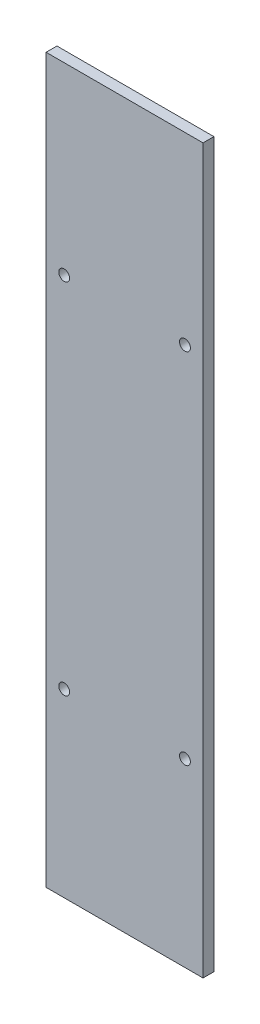
SolidWorks part; units mm, degrees
ref_plane "正面" through (0, 0, 0) normal (0, 0, 1) x (1, 0, 0)
ref_plane "平面" through (0, 0, 0) normal (0, 1, 0) x (1, 0, 0)
ref_plane "右側面" through (0, 0, 0) normal (1, 0, 0) x (0, 0, -1)
sketch "ｽｹｯﾁ1" plane through (0, 0, 0) normal (0, 0, 1) x (1, 0, 0)
  line L0 (0, 0) -> (0, 49.5573) construction
  line L1 (16.7, -49.5573) -> (-16.7, -49.5573) construction
  line L2 (16.7, -49.5573) -> (16.7, 49.5573) construction
  line L3 (16.7, 49.5573) -> (-16.7, 49.5573) construction
  line L4 (-16.7, -49.5573) -> (-16.7, 49.5573) construction
  line L5 (16.7, -49.5573) -> (-16.7, 49.5573) construction
  line L6 (16.7, 49.5573) -> (-16.7, -49.5573) construction
  line L8 (21.7, 100.4427) -> (-21.7, 100.4427)
  line L9 (21.7, 100.4427) -> (21.7, -99.5573)
  line L10 (21.7, -99.5573) -> (-21.7, -99.5573)
  line L11 (-21.7, 100.4427) -> (-21.7, -99.5573)
  line L12 (21.7, 100.4427) -> (-21.7, -99.5573) construction
  line L13 (21.7, -99.5573) -> (-21.7, 100.4427) construction
  circle A0 centre (-16.7, 49.5573) radius 1.5
  circle A1 centre (-16.7, -49.5573) radius 1.5
  circle A2 centre (16.7, -49.5573) radius 1.5
  circle A3 centre (16.7, 49.5573) radius 1.5
  point P0 (0, 0)
  point P12 (0, 0.4427)
  dimension "D3" = 3
  dimension "D1" = 99.1146
  dimension "D2" = 33.4
  dimension "D4" = 5
  dimension "D5" = 50
  dimension "D6" = 200
extrude "ﾎﾞｽ - 押し出し1" add sketch "ｽｹｯﾁ1" along normal blind 3
